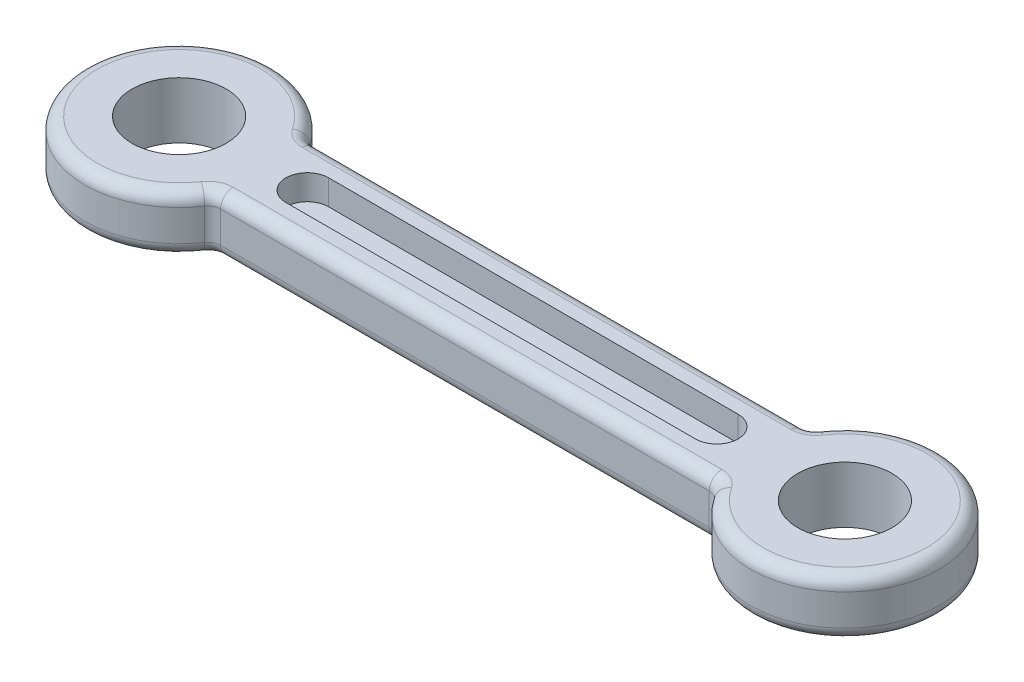
SolidWorks part; units mm, degrees
ref_plane "Front Plane" through (0, 0, 0) normal (0, 0, 1) x (1, 0, 0)
ref_plane "Top Plane" through (0, 0, 0) normal (0, 1, 0) x (1, 0, 0)
ref_plane "Right Plane" through (0, 0, 0) normal (1, 0, 0) x (0, 0, -1)
sketch "Sketch1" plane through (0, 0, 0) normal (0, 1, 0) x (1, 0, 0)
  line L0 (0, -55) -> (0, 55) construction
  line L1 (-101.6, 19.05) -> (101.6, 19.05)
  line L3 (-101.6, -19.05) -> (101.6, -19.05)
  line L5 (-101.6, 19.05) -> (0, 0) construction
  line L6 (0, 0) -> (101.6, 19.05) construction
  arc A0 (-101.6, 19.05) -> (-101.6, -19.05) centre (-134.5956, 0) ccw
  circle A1 centre (-134.5956, 0) radius 19.05
  circle A2 centre (134.5956, 0) radius 19.05
  arc A3 (101.6, 19.05) -> (101.6, -19.05) centre (134.5956, 0) cw
  point P0 (0, 0)
  point P14 (0, 0)
  point P15 (-139.7, 0)
  point P16 (-131.9408, 0)
  dimension "D3" = 76.2
  dimension "D4" = 38.1
  dimension "D1" = 203.2
  dimension "D2" = 38.1
extrude "Boss-Extrude1" add sketch "Sketch1" along normal mid plane 22.86
sketch "Sketch2" plane through (0, 11.43, 0) normal (0, 1, 0) x (1, 0, 0)
  line L0 (-82.7792, 0) -> (82.7792, 0) construction
  line L1 (-82.7792, 8.6458) -> (82.7792, 8.6458)
  line L2 (-82.7792, -8.6458) -> (82.7792, -8.6458)
  arc A0 (-82.7792, 8.6458) -> (-82.7792, -8.6458) centre (-82.7792, 0) ccw
  arc A1 (82.7792, -8.6458) -> (82.7792, 8.6458) centre (82.7792, 0) ccw
  point P3 (0, 0)
  point P8 (39.734, 0)
  point P9 (-82.7792, 0)
  point P10 (0, 0)
  point P11 (82.7792, 0)
extrude "Cut-Extrude1" cut sketch "Sketch2" against normal blind 10.16
mirror "Mirror2" about plane through (0, 0, 0) normal (0, 1, 0) of "Cut-Extrude1"
fillet "Fillet1" radius 5.08 4 edges at (-101.6, 0, -19.05) (-101.6, 0, 19.05) (101.6, 0, 19.05) (101.6, 0, -19.05)
fillet "Fillet2" radius 5.08 16 edges at (-101.1729, -11.43, -19.6452) (0, -11.43, -19.05) (101.1729, -11.43, -19.6452) (172.6956, -11.43, 0) (101.1729, -11.43, 19.6452) (0, -11.43, 19.05) (-101.1729, -11.43, 19.6452) (101.1729, 11.43, 19.6452) (0, 11.43, 19.05) (-101.1729, 11.43, 19.6452) (-172.6956, 11.43, 0) (-101.1729, 11.43, -19.6452) (0, 11.43, -19.05) (101.1729, 11.43, -19.6452) (-172.6956, -11.43, 0) (172.6956, 11.43, 0)
